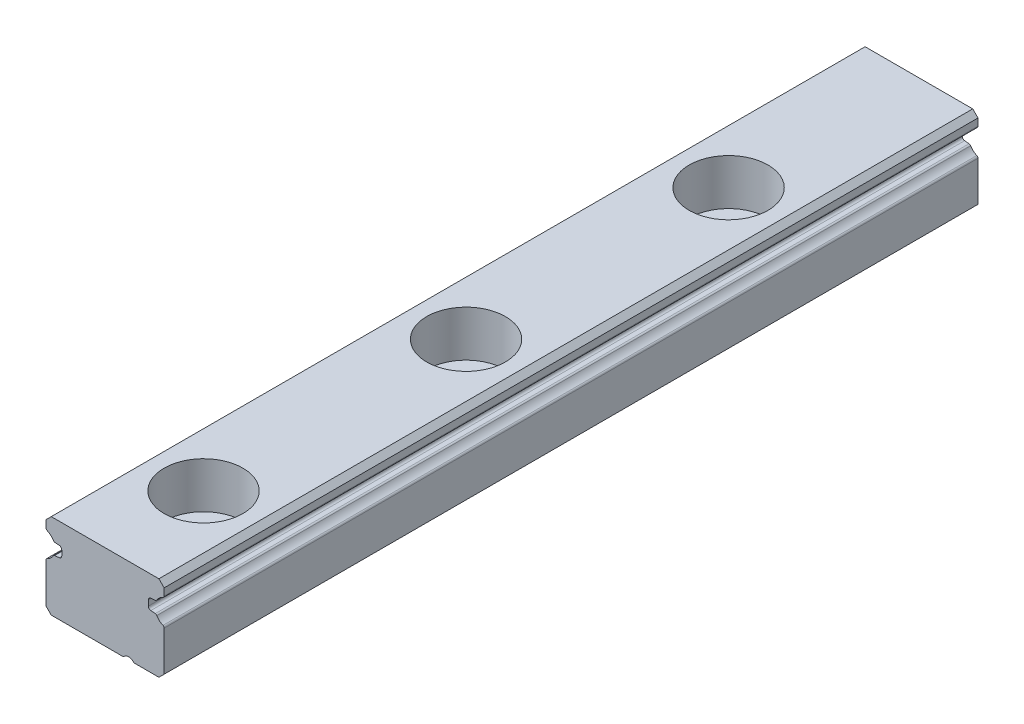
SolidWorks part; units mm, degrees
ref_plane "Front Plane" through (0, 0, 0) normal (0, 0, 1) x (1, 0, 0)
ref_plane "Top Plane" through (0, 0, 0) normal (0, 1, 0) x (1, 0, 0)
ref_plane "Right Plane" through (0, 0, 0) normal (1, 0, 0) x (0, 0, -1)
sketch "Sketch1" plane through (0, 0, 0) normal (0, 0, 1) x (1, 0, 0)
  line L0 (-4.5, 0) -> (4.5, 0) construction
  line L1 (0, -3.25) -> (0, 3.25) construction
  line L2 (0, 3.25) -> (0, -3.25) construction
  line L3 (-3, 3.25) -> (3, 3.25) construction
  line L4 (-1.75, -0.25) -> (1.75, -0.25) construction
  point P0 (0, -0.25)
  point P3 (-4.5, -3.25)
  point P4 (0, 0)
  point P8 (0, 0)
  point P11 (0, 3.25)
  point P15 (0, 3.25)
  point P17 (0, -0.25)
  point P18 (4.5, 3.25)
  point P20 (-4.5, 3.25)
  dimension "Rail Width" = 9
  dimension "Rail Height" = 6.5
  dimension "Mounting Hole Depth" = 3
  dimension "Mounting Hole Counterbore Diameter" = 6
  dimension "Mounting Hole Diameter" = 3.5
sketch "Sketch2" plane through (0, 0, 0) normal (1, 0, 0) x (0, 0, -1)
  line L0 (31, 0) -> (-31, 0) construction
  line L1 (-1.5, 3.25) -> (1.5, 3.25) construction
  line L3 (0, 3.25) -> (0, 0) construction
  point P0 (-23.5, 0)
  point P4 (0, 0)
  point P5 (-3.5, 0)
  point P6 (-13.5, 0)
  point P9 (-23.5, 3.25)
  point P10 (0, 3.25)
  point P11 (31, 3.25)
  point P13 (-31, 3.25)
  point P14 (13.5, 0)
  point P17 (-31, -3.25)
  dimension "Rail Length" = 62
  dimension "Mounting Hole Center to Edge" = 7.5
  dimension "Mounting Hole Center to Center" = 20
  dimension "Number of Mounting Holes" = 3
  dimension "Break Line" = 10
sketch "Sketch3" plane through (0, 0, 0) normal (0, 0, 1) x (1, 0, 0)
  point P0 (0, 3.25)
  line B0 (-4.5, 0.1917) -> (-4.5, -2.85)
  line B1 (-4.5, -2.85) -> (-4.1, -3.25)
  line B2 (-4.1, -3.25) -> (1.4, -3.25)
  line B3 (2.2, -3.25) -> (4.1, -3.25)
  line B4 (4.1, -3.25) -> (4.5, -2.85)
  line B5 (4.5, -2.85) -> (4.5, 0.1917)
  line B6 (3.8235, 0.8135) -> (3.4826, 0.8434)
  line B7 (3.3, 1.0426) -> (3.3, 1.4574)
  line B8 (3.4826, 1.6566) -> (3.8235, 1.6865)
  line B9 (4.5, 2.3083) -> (4.5, 2.85)
  line B10 (4.5, 2.85) -> (4.1, 3.25)
  line B11 (4.1, 3.25) -> (-4.1, 3.25)
  line B12 (-4.1, 3.25) -> (-4.5, 2.85)
  line B13 (-4.5, 2.85) -> (-4.5, 2.3083)
  line B14 (-3.8235, 1.6865) -> (-3.4826, 1.6566)
  line B15 (-3.3, 1.4574) -> (-3.3, 1.0426)
  line B16 (-3.4826, 0.8434) -> (-3.8235, 0.8135)
  arc B17 (2.2, -3.25) -> (1.4, -3.25) centre (1.8, -3.55) ccw
  arc B18 (4.5, 0.1917) -> (4.4087, 0.3297) centre (4.35, 0.1917) ccw
  arc B19 (3.9395, 0.7405) -> (4.4087, 0.3297) centre (4.8, 1.25) ccw
  arc B20 (3.9395, 0.7405) -> (3.8235, 0.8135) centre (3.8104, 0.6641) ccw
  arc B21 (3.3, 1.0426) -> (3.4826, 0.8434) centre (3.5, 1.0426) ccw
  arc B22 (3.4826, 1.6566) -> (3.3, 1.4574) centre (3.5, 1.4574) ccw
  arc B23 (3.8235, 1.6865) -> (3.9395, 1.7595) centre (3.8104, 1.8359) ccw
  arc B24 (4.4087, 2.1703) -> (3.9395, 1.7595) centre (4.8, 1.25) ccw
  arc B25 (4.4087, 2.1703) -> (4.5, 2.3083) centre (4.35, 2.3083) ccw
  arc B26 (-4.5, 2.3083) -> (-4.4087, 2.1703) centre (-4.35, 2.3083) ccw
  arc B27 (-3.9395, 1.7595) -> (-4.4087, 2.1703) centre (-4.8, 1.25) ccw
  arc B28 (-3.9395, 1.7595) -> (-3.8235, 1.6865) centre (-3.8104, 1.8359) ccw
  arc B29 (-3.3, 1.4574) -> (-3.4826, 1.6566) centre (-3.5, 1.4574) ccw
  arc B30 (-3.4826, 0.8434) -> (-3.3, 1.0426) centre (-3.5, 1.0426) ccw
  arc B31 (-3.8235, 0.8135) -> (-3.9395, 0.7405) centre (-3.8104, 0.6641) ccw
  arc B32 (-4.4087, 0.3297) -> (-3.9395, 0.7405) centre (-4.8, 1.25) ccw
  arc B33 (-4.4087, 0.3297) -> (-4.5, 0.1917) centre (-4.35, 0.1917) ccw
sketch_block_instance "9mm Block-1"
sketch_block "9mm Block"
extrude "Boss-Extrude1" add sketch "Sketch3" against normal up to vertex (31 mm away) from vertex at 31 starting at point (0, 0, 31)
ref_plane "Plane1" through (0, 0, 23.5) normal (0, 0, 1) x (1, 0, 0)
sketch "Sketch4" plane through (0, 0, 23.5) normal (0, 0, 1) x (1, 0, 0)
  line L0 (0, 3.25) -> (0, -3.25)
  line L1 (0, -3.25) -> (-1.75, -3.25)
  line L3 (-1.75, -3.25) -> (-1.75, -0.25)
  line L4 (-1.75, -0.25) -> (-3, -0.25)
  line L5 (-3, -0.25) -> (-3, 3.25)
  line L6 (-3, 3.25) -> (0, 3.25)
revolve "Cut-Revolve1" cut sketch "Sketch4" angle 360 about L0
sketch "Sketch6" plane through (0, 0, 0) normal (1, 0, 0) x (0, 0, -1)
  line L0 (-20.5, -0.25) -> (-26.5, -0.25) construction
  line L5 (-20.5, -0.25) -> (-26.5, -0.25)
  line L17 (-25.25, -0.25) -> (-25.25, -3.25) construction
  line L18 (-21.75, -3.25) -> (-21.75, -0.25) construction
  line L32 (-20.5, -0.25) -> (-20.5, 3.25) construction
  line L33 (-26.5, 3.25) -> (-26.5, -0.25) construction
  line L34 (-25.25, -0.25) -> (-25.25, -3.25)
  line L35 (-21.75, -3.25) -> (-21.75, -0.25)
  line L36 (-20.5, -0.25) -> (-20.5, 3.25)
  line L37 (-26.5, 3.25) -> (-26.5, -0.25)
  line L38 (0, 3.25) -> (0, -3.25) construction
  line L40 (26.5, 3.25) -> (26.5, -0.25)
  line L41 (20.5, -0.25) -> (20.5, 3.25)
  line L42 (21.75, -3.25) -> (21.75, -0.25)
  line L43 (25.25, -0.25) -> (25.25, -3.25)
  line L44 (20.5, -0.25) -> (26.5, -0.25)
sketch "Sketch7" plane through (0, 0, 0) normal (0, 0, 1) x (1, 0, 0)
  line L0 (3, -0.25) -> (3, 3.25) construction
  line L1 (-3, 3.25) -> (-3, -0.25) construction
  line L2 (3, -0.25) -> (3, 3.25)
  line L3 (-3, 3.25) -> (-3, -0.25)
  line L4 (1.75, -3.0525) -> (1.75, -0.25) construction
  line L11 (1.75, -3.0525) -> (1.75, -0.25)
  line L18 (-1.75, -0.25) -> (-1.75, -3.25) construction
  line L32 (3, -0.25) -> (-3, -0.25) construction
  line L34 (-1.75, -0.25) -> (-1.75, -3.25)
  line L37 (3, -0.25) -> (-3, -0.25)
pattern_linear "LPattern1" count 3 spacing 20 along (0, 0, -1) of "Cut-Revolve1"
equation "\"D3@LPattern1\"=\"Mounting Hole Center to Center@Sketch2\""
equation "\"Break Line@Sketch2\"=\"Mounting Hole Center to Center@Sketch2\"/2"
